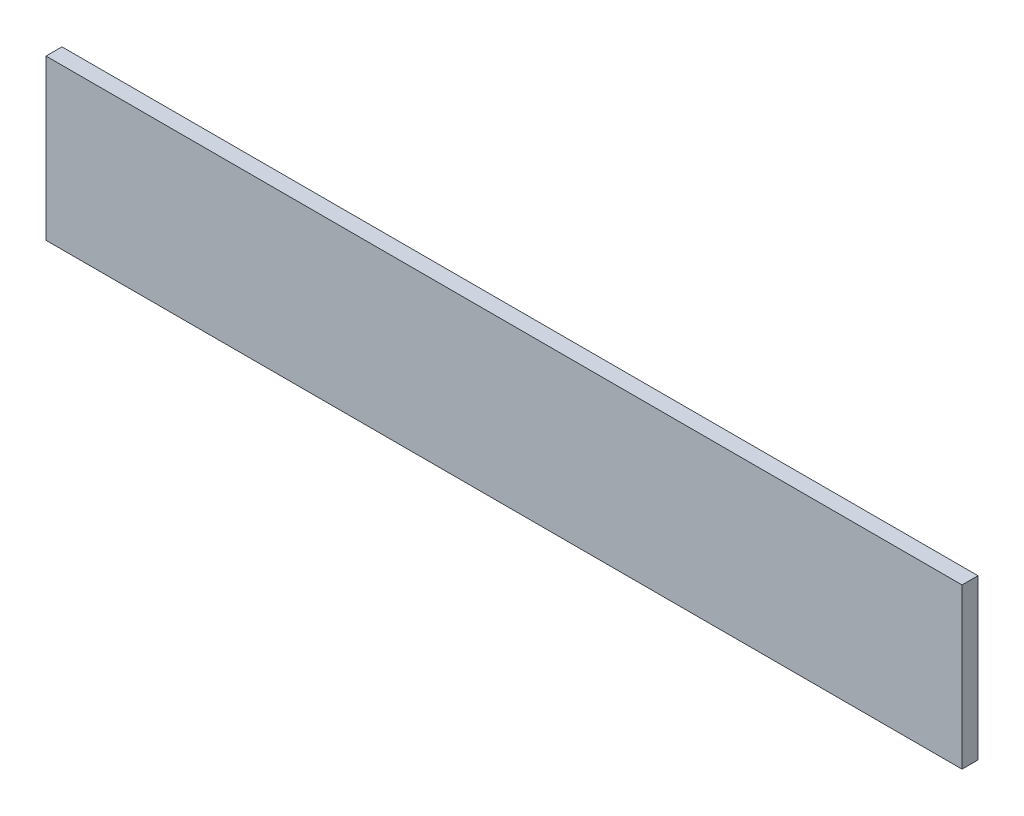
SolidWorks part; units mm, degrees
ref_plane "Front Plane" through (0, 0, 0) normal (0, 0, 1) x (1, 0, 0)
ref_plane "Top Plane" through (0, 0, 0) normal (0, 1, 0) x (1, 0, 0)
ref_plane "Right Plane" through (0, 0, 0) normal (1, 0, 0) x (0, 0, -1)
sketch "Sketch1" plane through (0, 0, 0) normal (0, 0, 1) x (1, 0, 0)
  line L1 (-287, 50) -> (287, 50)
  line L2 (-287, 50) -> (-287, -50)
  line L3 (-287, -50) -> (287, -50)
  line L4 (287, 50) -> (287, -50)
  dimension "D1" = 574
  dimension "D2" = 100
  dimension "D3" = 287
  dimension "D4" = 50
extrude "Boss-Extrude1" add sketch "Sketch1" along normal blind 10
